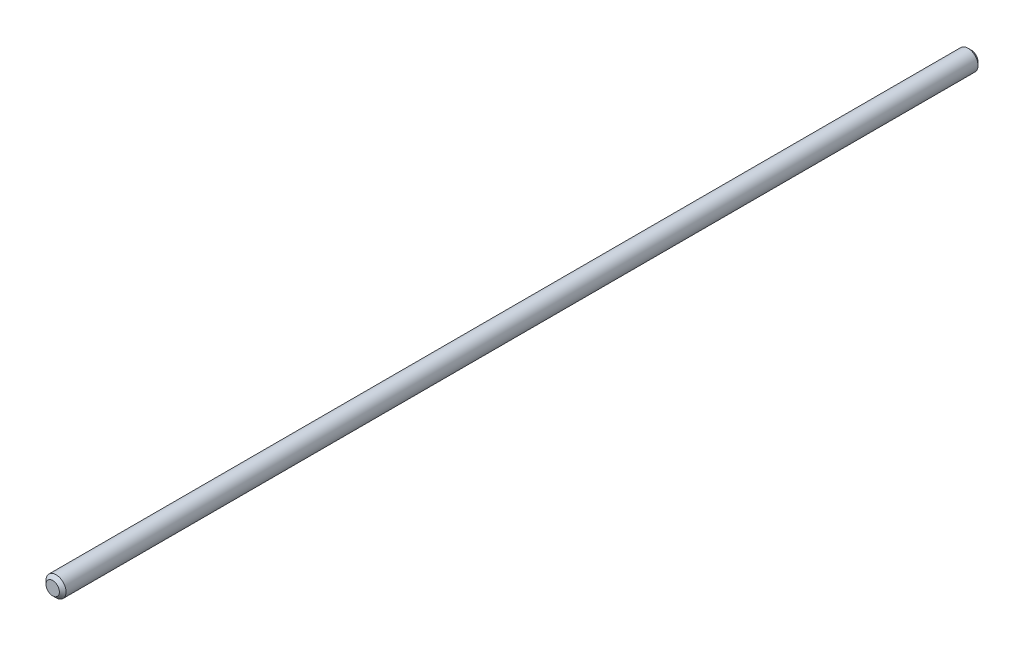
SolidWorks part; units mm, degrees
material "Plain Carbon Steel"
ref_plane "Спереди" through (0, 0, 0) normal (0, 0, 1) x (1, 0, 0)
ref_plane "Сверху" through (0, 0, 0) normal (0, 1, 0) x (1, 0, 0)
ref_plane "Справа" through (0, 0, 0) normal (1, 0, 0) x (0, 0, -1)
sketch "Sketch1" plane through (0, 0, 0) normal (0, 0, 1) x (1, 0, 0)
  circle A0 centre (0, 0) radius 3
  dimension "D1" = 6
extrude "Boss-Extrude1" add sketch "Sketch1" along normal blind 275
chamfer "Chamfer1" distance 1 angle 45 2 edges at (3, 0, 275) (3, 0, 0)
